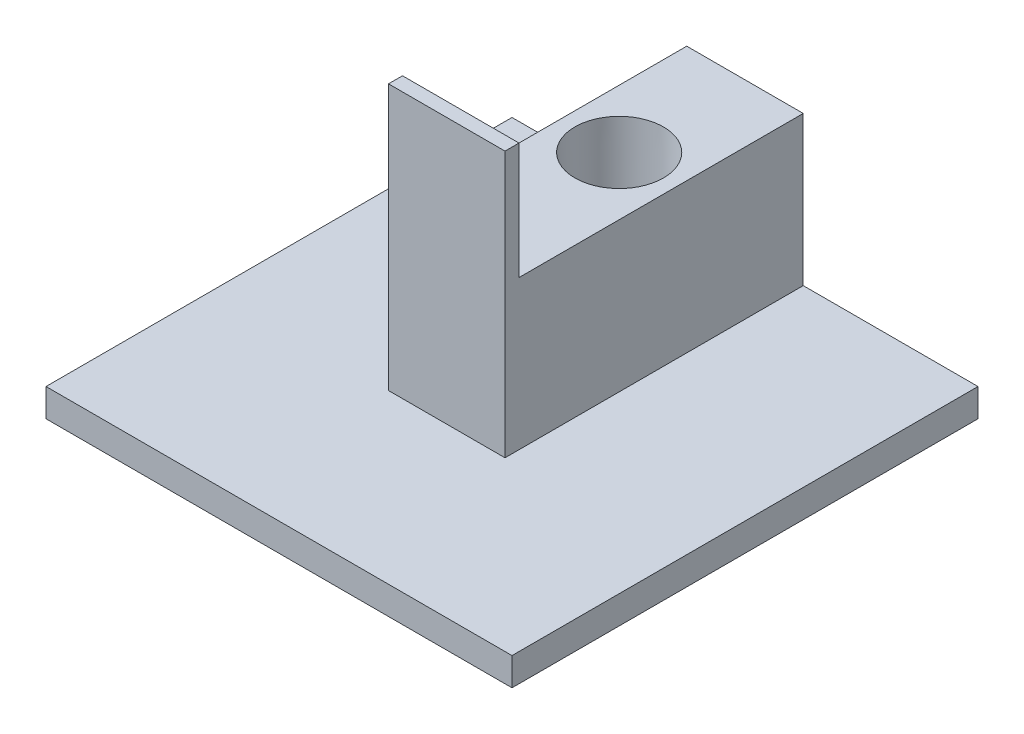
SolidWorks part; units mm, degrees
ref_plane "Front Plane" through (0, 0, 0) normal (0, 0, 1) x (1, 0, 0)
ref_plane "Top Plane" through (0, 0, 0) normal (0, 1, 0) x (1, 0, 0)
ref_plane "Right Plane" through (0, 0, 0) normal (1, 0, 0) x (0, 0, -1)
sketch "Sketch1" plane through (0, 0, 0) normal (0, 1, 0) x (1, 0, 0)
  line L0 (-48.75, 25.7143) -> (51.25, -74.2857) construction
  line L1 (-48.75, 25.7143) -> (51.25, 25.7143)
  line L2 (-48.75, 25.7143) -> (-48.75, -74.2857)
  line L3 (-48.75, -74.2857) -> (51.25, -74.2857)
  line L4 (51.25, 25.7143) -> (51.25, -74.2857)
  line L5 (51.25, 25.7143) -> (-48.75, -74.2857) construction
  dimension "D1" = 100
  dimension "D2" = 100
extrude "Boss-Extrude1" add sketch "Sketch1" along normal blind 38
sketch "Sketch3" plane through (0, 0, 0) normal (0, -1, 0) x (1, 0, 0)
  line L0 (-48.75, 74.2857) -> (51.25, -25.7143) construction
  line L1 (51.25, 74.2857) -> (-48.75, -25.7143) construction
  circle A0 centre (-27.0343, 52.57) radius 3
  circle A1 centre (29.5343, 52.57) radius 3
  circle A2 centre (29.5343, -3.9986) radius 3
  circle A3 centre (-27.0343, -3.9986) radius 3
  point P10 (1.25, 24.2857)
  point P20 (1.25, 24.2857)
  dimension "D1" = 6
  dimension "D2" = 40
  dimension "D3" = 4
extrude "Boss-Extrude2" add sketch "Sketch3" along normal blind 3
sketch "Sketch4" plane through (0, 0, 0) normal (0, -1, 0) x (1, 0, 0)
  line L0 (-48.75, 74.2857) -> (51.25, -25.7143) construction
  line L1 (51.25, 74.2857) -> (-48.75, -25.7143) construction
  line L2 (1.25, 18.7992) -> (1.25, 53.1215) construction
  circle A0 centre (1.25, 1.2857) radius 8.25
  point P8 (1.25, 24.2857)
  dimension "D1" = 16.5
  dimension "D2" = 23
sketch "Sketch5" plane through (0, 38, 0) normal (0, 1, 0) x (1, 0, 0)
  circle A0 centre (1.25, -1.2857) radius 9.5
  dimension "D1" = 19
loft "Cut-Loft1" cut profiles "Sketch4", "Sketch5"
sketch "Sketch6" plane through (0, 38, 0) normal (0, 1, 0) x (1, 0, 0)
  line L0 (1.25, 6.9643) -> (43.234, 6.9643) construction
  line L5 (-11.25, -35.2857) -> (13.75, -35.2857)
  line L6 (-11.25, -35.2857) -> (-11.25, -38.2857)
  line L7 (-11.25, -38.2857) -> (13.75, -38.2857)
  line L8 (13.75, -35.2857) -> (13.75, -38.2857)
  line L9 (1.25, 6.9643) -> (1.25, -54.9835) construction
  circle A1 centre (1.25, -1.2857) radius 8.25 construction
  dimension "D1" = 34
  dimension "D2" = 3
  dimension "D3" = 25
extrude "Boss-Extrude3" add sketch "Sketch6" along normal blind 25
sketch "Sketch9" plane through (0, 38, 0) normal (0, 1, 0) x (1, 0, 0)
  line L0 (-11.25, -35.2857) -> (-11.25, -38.2857) construction
  line L1 (-49.7997, 27.7514) -> (-11.25, 27.7514)
  line L2 (-49.7997, 27.7514) -> (-49.7997, -78.7385)
  line L3 (-49.7997, -78.7385) -> (-21.6003, -78.7385)
  line L4 (-11.25, 27.7514) -> (-11.25, -38.2857)
  line L5 (53.4069, 28.5566) -> (13.75, 28.5566)
  line L6 (53.4069, 28.5566) -> (53.4069, -79.3424)
  line L7 (53.4069, -79.3424) -> (26.1849, -79.3424)
  line L8 (13.75, 28.5566) -> (13.75, -38.2857)
  line L9 (13.75, -38.2857) -> (13.75, -35.2857) construction
  line L10 (-11.25, -38.2857) -> (13.75, -38.2857) construction
  line L11 (-11.25, -38.2857) -> (13.75, -38.2857)
  line L12 (-21.6003, -78.7385) -> (-21.6003, -84.0383)
  line L13 (-21.6003, -84.0383) -> (26.1849, -84.0383)
  line L14 (26.1849, -79.3424) -> (26.1849, -84.0383)
  dimension "D1" = 0
  dimension "D2" = 0
  dimension "D3" = 0
extrude "Cut-Extrude3" cut sketch "Sketch9" against normal blind 32
